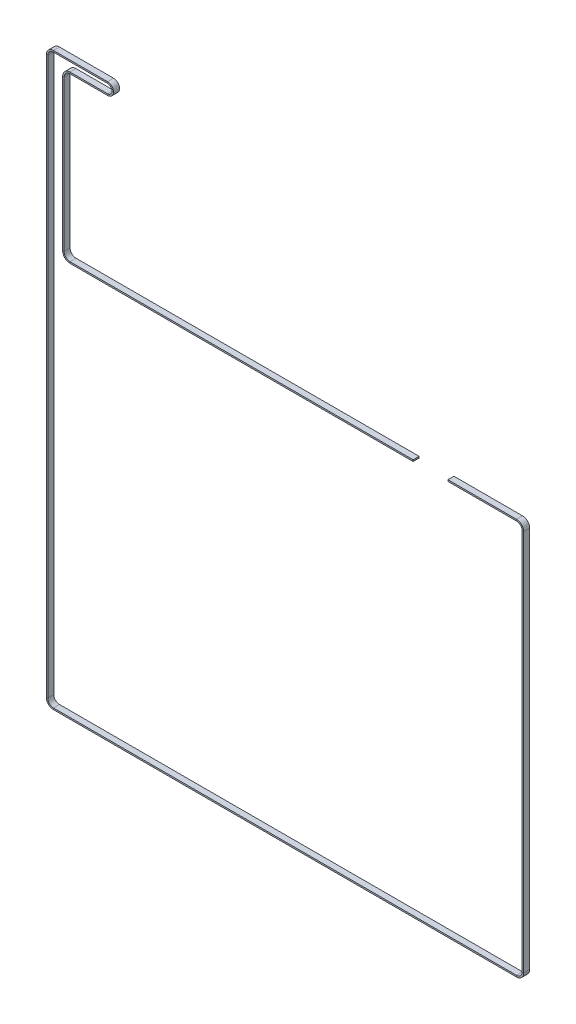
SolidWorks part; units mm, degrees
ref_plane "Front" through (0, 0, 0) normal (0, 0, 1) x (1, 0, 0)
ref_plane "Top" through (0, 0, 0) normal (0, 1, 0) x (1, 0, 0)
ref_plane "Right" through (0, 0, 0) normal (1, 0, 0) x (0, 0, -1)
sketch "Sketch1" plane through (0, -21, 4.45) normal (0, 0, 1) x (1, 0, 0)
  line L0 (10, 63.3) -> (47.5, 63.3)
  line L1 (47.5, 73.7) -> (-6.5, 73.7)
  line L2 (-12.875, 67.325) -> (-12.875, -488)
  line L3 (-6.5, -494.375) -> (455.5, -494.375)
  line L4 (461.875, -488) -> (461.875, -106.7715)
  line L5 (455.5, -100.3965) -> (387.0556, -100.3965)
  line L7 (3.4, 56.7) -> (3.4, -93.9465)
  line L8 (10, -100.5465) -> (352.3556, -100.5465)
  line L10 (352.3556, -100.4465) -> (352.3556, -103.9465) construction
  line L11 (387.0556, -99.9465) -> (387.0556, -92.9465) construction
  circle A0 centre (47.5, 68.5) radius 5.2 construction
  circle A1 centre (10, 56.7) radius 6.6 construction
  circle A2 centre (-6.5, 67.325) radius 6.375 construction
  circle A3 centre (10, -93.9465) radius 6.6 construction
  circle A4 centre (-6.5, -488) radius 6.375 construction
  circle A5 centre (455.5, -488) radius 6.375 construction
  circle A6 centre (455.5, -106.7715) radius 6.375 construction
  arc A7 (47.5, 73.7) -> (47.5, 63.3) centre (47.5, 68.5) cw
  arc A8 (10, 63.3) -> (3.4, 56.7) centre (10, 56.7) ccw
  arc A9 (-12.875, 67.325) -> (-6.5, 73.7) centre (-6.5, 67.325) cw
  arc A10 (-6.5, -494.375) -> (-12.875, -488) centre (-6.5, -488) cw
  arc A11 (455.5, -494.375) -> (461.875, -488) centre (455.5, -488) ccw
  arc A12 (461.875, -106.7715) -> (455.5, -100.3965) centre (455.5, -106.7715) ccw
  arc A13 (3.4, -93.9465) -> (10, -100.5465) centre (10, -93.9465) ccw
  circle A14 centre (-6.5, 67.325) radius 9 construction
  dimension "D1" = 12.75
ref_plane "Plane1" through (387.0556, -121.3965, 4.45) normal (-1, 0, 0) x (0, 0, 1)
sketch "Sketch2" plane through (387.0556, -121.3965, 4.45) normal (-1, 0, 0) x (0, 0, 1)
  line L1 (-3, 0.75) -> (3, 0.75)
  line L2 (-3, 0.75) -> (-3, -0.75)
  line L3 (-3, -0.75) -> (3, -0.75)
  line L4 (3, 0.75) -> (3, -0.75)
  line L5 (-3, 0.75) -> (3, -0.75) construction
  line L6 (-3, -0.75) -> (3, 0.75) construction
  point P0 (0, 0)
  dimension "D1" = 6
  dimension "D2" = 1.5
sweep "Sweep1" add profiles "Sketch2" path "Sketch1"
